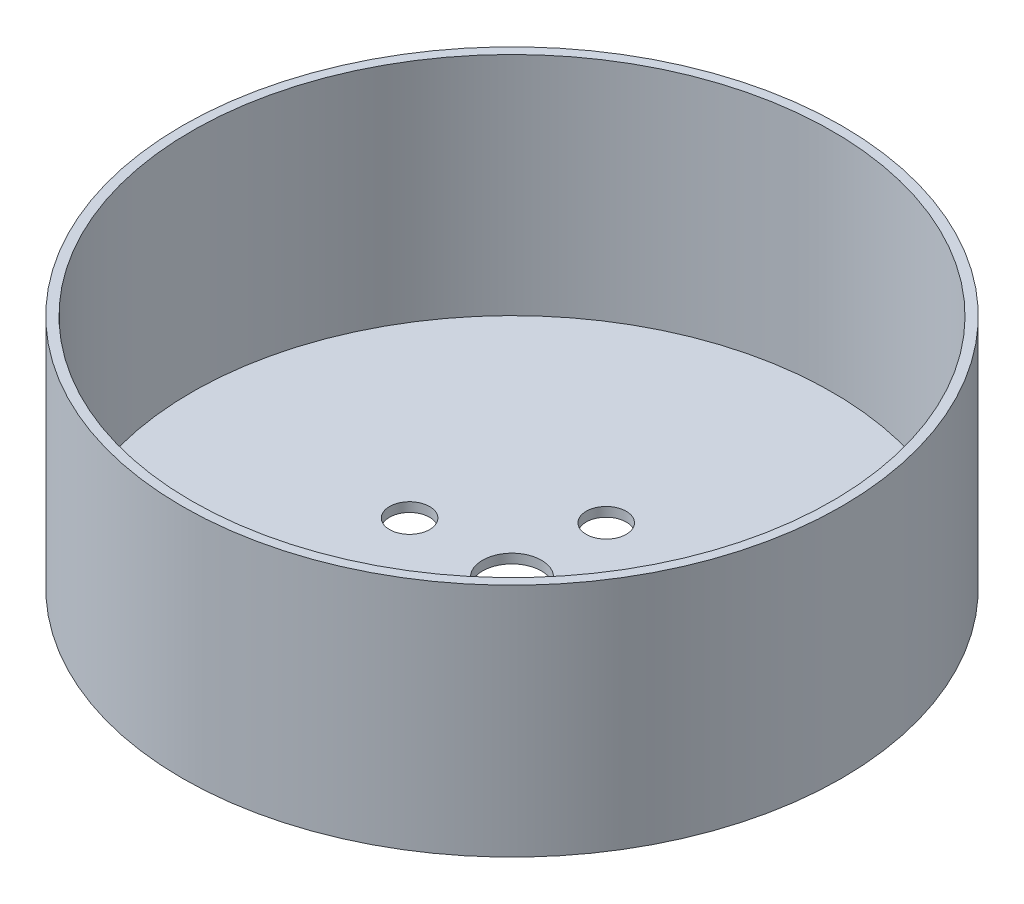
SolidWorks part; units mm, degrees
ref_plane "Front Plane" through (0, 0, 0) normal (0, 0, 1) x (1, 0, 0)
ref_plane "Top Plane" through (0, 0, 0) normal (0, 1, 0) x (1, 0, 0)
ref_plane "Right Plane" through (0, 0, 0) normal (1, 0, 0) x (0, 0, -1)
sketch "Sketch1" plane through (0, 0, 0) normal (0, 1, 0) x (1, 0, 0)
  circle A0 centre (0, 0) radius 28
  dimension "D1" = 56
extrude "Boss-Extrude1" add sketch "Sketch1" along normal blind 20
sketch "Sketch2" plane through (0, 20, 0) normal (0, 1, 0) x (1, 0, 0)
  circle A0 centre (0, 0) radius 27.2063
  circle A1 centre (0, 0) radius 28 construction
  dimension "D1" = 0.7937
extrude "Cut-Extrude1" cut sketch "Sketch2" against normal offset from surface (19.2063 mm away) 0.7937 up to face at (0, 0, 28)
hole_wizard "M3 Clearance Hole1" positions "Sketch4" profile "Sketch3" hole size "M3" standard "ANSI Metric"
sketch "Sketch4" plane through (0, 0, 0) normal (0, -1, 0) x (-1, 0, 0)
  line L1 (7.937, 9.6057) -> (0, 0)
  line L2 (0, 0) -> (-7.7691, -9.4026)
  line L5 (-9.3268, 7.7065) -> (9.3487, -7.7246)
  circle A0 centre (0, 0) radius 8.7
  circle A1 centre (0, 0) radius 8
  point P13 (8.1078, 3.155)
  point P14 (-8.1078, -3.155)
  point P45 (0, 8)
  point P47 (0, -8)
  point P49 (-8.7, 0)
  point P51 (8.7, 0)
sketch "Sketch3" plane through (0, 0, -8) normal (1, 0, 0) x (0, 0, -1)
  line L0 (0, 0) -> (0, 20)
  line L1 (0, 20) -> (1.7, 20)
  line L2 (1.7, 20) -> (1.7, 0)
  line L5 (1.7, 0) -> (0, 0)
  line L11 (0, -6.35) -> (0, 107.95) construction
  dimension "Thru Hole Dia." = 3.4
  dimension "Thru Hole Depth" = 20
sketch "Sketch5" plane through (0, 0, 0) normal (0, -1, 0) x (1, 0, 0)
  circle A0 centre (0, 0) radius 2.5
  dimension "D1" = 5
extrude "Cut-Extrude2" cut sketch "Sketch5" against normal through all
